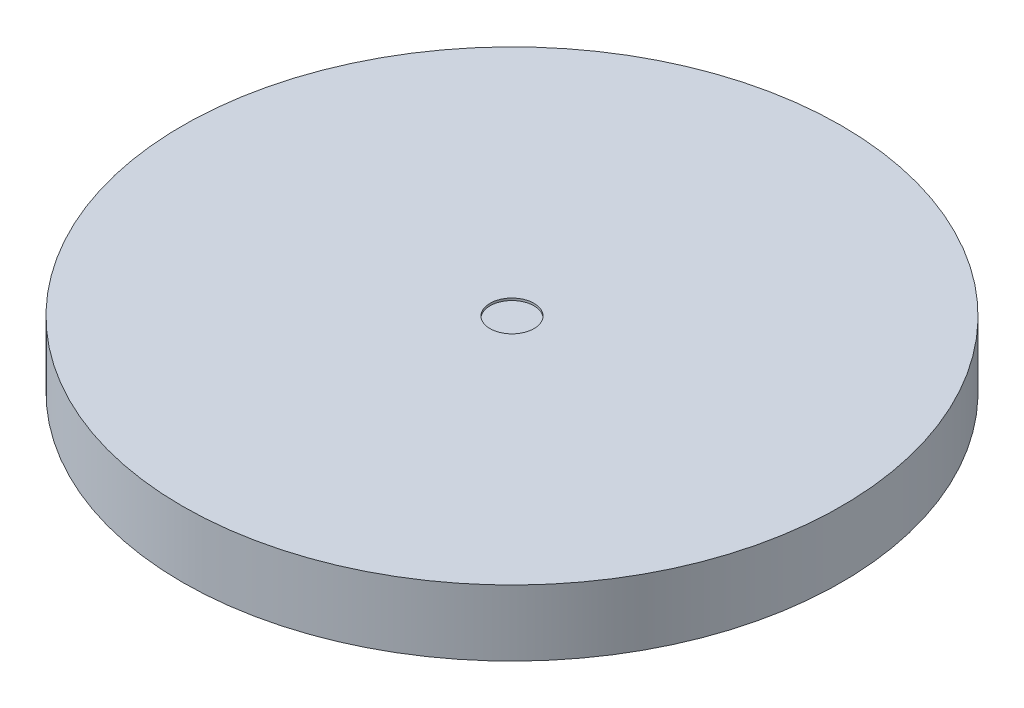
SolidWorks part; units mm, degrees
ref_plane "Front Plane" through (0, 0, 0) normal (0, 0, 1) x (1, 0, 0)
ref_plane "Top Plane" through (0, 0, 0) normal (0, 1, 0) x (1, 0, 0)
ref_plane "Right Plane" through (0, 0, 0) normal (1, 0, 0) x (0, 0, -1)
sketch "Sketch1" plane through (0, 0, 0) normal (0, 1, 0) x (1, 0, 0)
  circle A0 centre (0, 0) radius 30
extrude "Boss-Extrude1" add sketch "Sketch1" along normal blind 6
sketch "Sketch2" plane through (0, 6, 0) normal (0, 1, 0) x (1, 0, 0)
  circle A0 centre (0, 0) radius 2
extrude "Cut-Extrude1" cut sketch "Sketch2" against normal blind 0.2
